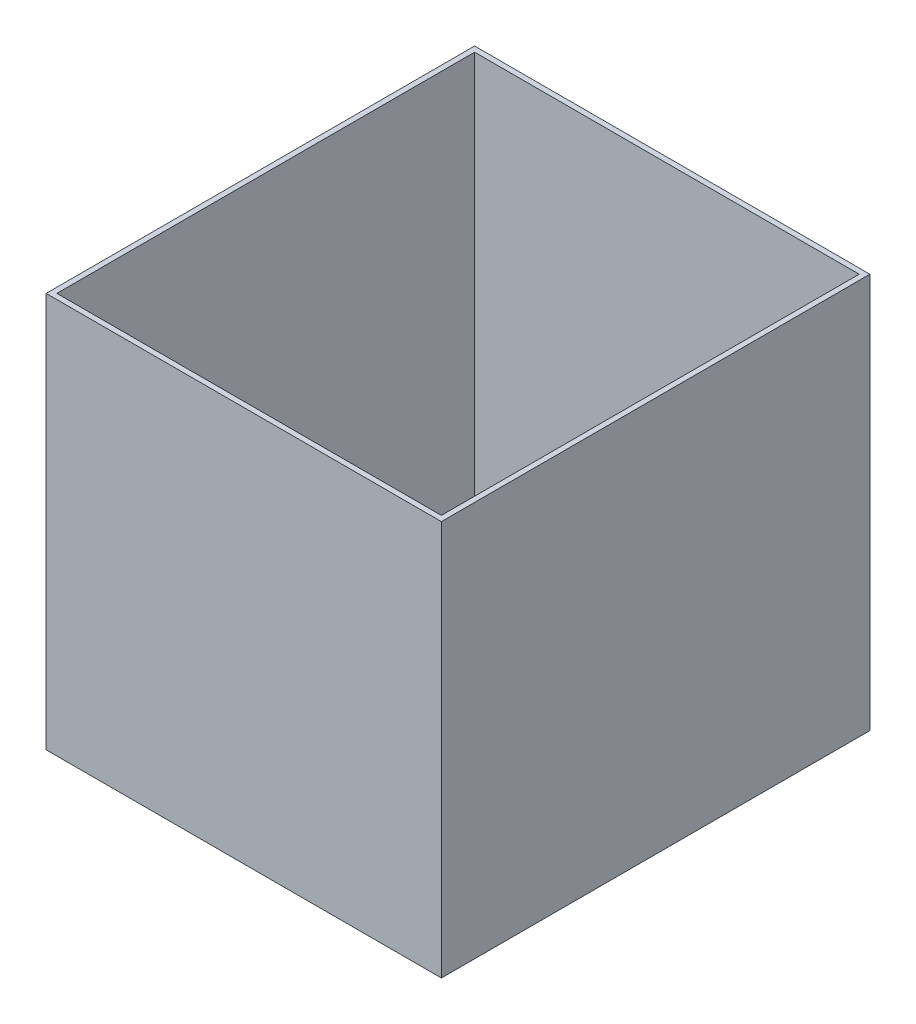
SolidWorks part; units mm, degrees
ref_plane "Plan de face" through (0, 0, 0) normal (0, 0, 1) x (1, 0, 0)
ref_plane "Plan de dessus" through (0, 0, 0) normal (0, 1, 0) x (1, 0, 0)
ref_plane "Plan de droite" through (0, 0, 0) normal (1, 0, 0) x (0, 0, -1)
sketch "Esquisse1" plane through (0, 0, 0) normal (0, 1, 0) x (1, 0, 0)
  line L0 (0, 0) -> (369, 0)
  line L1 (369, 0) -> (369, 400)
  line L2 (369, 400) -> (0, 400)
  line L3 (0, 400) -> (0, 0)
  dimension "D1" = 400
  dimension "D2" = 369
extrude "Boss.-Extru.1" add sketch "Esquisse1" along normal blind 369
shell "Coque1" thickness 5
